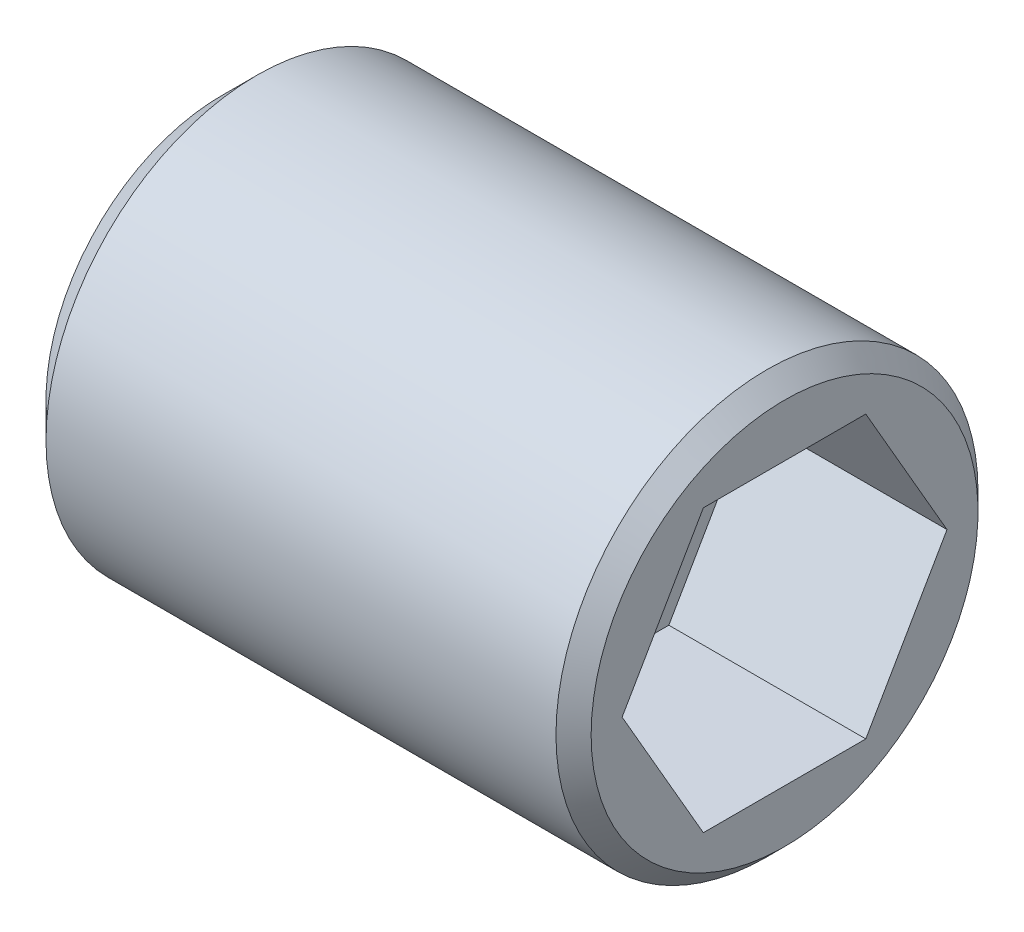
SolidWorks part; units mm, degrees
ref_plane "Plan1" through (0, 0, 0) normal (0, 0, 1) x (1, 0, 0)
ref_plane "Plan2" through (0, 0, 0) normal (0, 1, 0) x (1, 0, 0)
ref_plane "Plan3" through (0, 0, 0) normal (1, 0, 0) x (0, 0, -1)
sketch "Esquisse1" plane through (0, 0, 0) normal (0, 0, 1) x (1, 0, 0)
  line L0 (-25.8285, 0) -> (47.3208, 0) construction
  line L1 (0, 0) -> (0, 3)
  line L2 (0, 3) -> (8, 3)
  line L4 (8, 3) -> (8, 0)
  line L5 (8, 0) -> (0, 0)
  dimension "D1" = 6
  dimension "D2" = 8
revolve "Base-Révolution" add sketch "Esquisse1" angle 360 about L0
chamfer "Chanfrein2" distance 0.5 angle 45 1 edges at (0, 0, 3)
sketch "Esquisse2" plane through (8, 0, 0) normal (1, 0, 0) x (0, 0, -1)
  line L1 (2.3094, 0) -> (1.1547, 2)
  line L2 (1.1547, 2) -> (-1.1547, 2)
  line L3 (-1.1547, 2) -> (-2.3094, 0)
  line L4 (-2.3094, 0) -> (-1.1547, -2)
  line L5 (-1.1547, -2) -> (1.1547, -2)
  line L6 (1.1547, -2) -> (2.3094, 0)
  circle A0 centre (0, 0) radius 2 construction
  dimension "D1" = 4
extrude "Empreinte pour clé" cut sketch "Esquisse2" against normal blind 2.8
chamfer "Chanfrein3" distance 0.25 angle 45 1 edges at (8, 0, 3)
